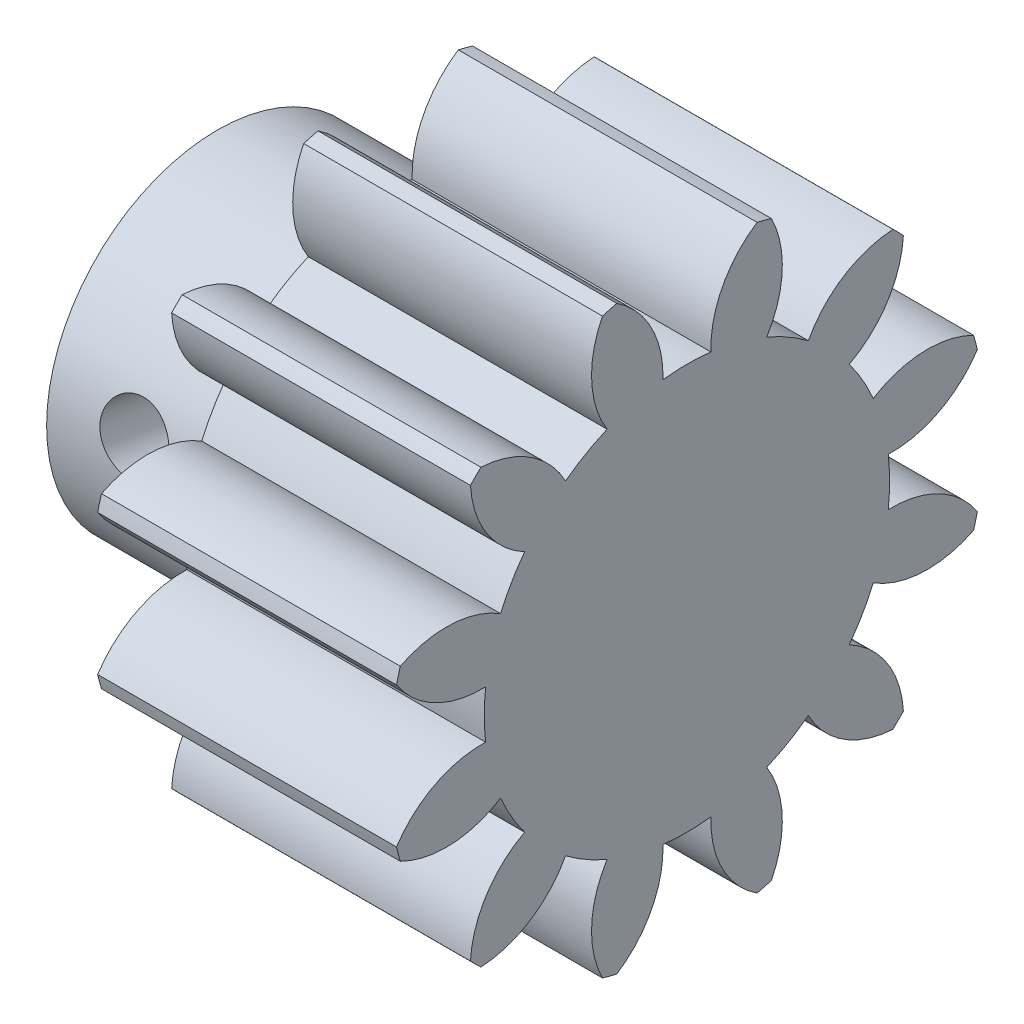
SolidWorks part; units mm, degrees
ref_plane "Plane1" through (0, 0, 0) normal (0, 0, 1) x (1, 0, 0)
ref_plane "Plane2" through (0, 0, 0) normal (0, 1, 0) x (1, 0, 0)
ref_plane "Plane3" through (0, 0, 0) normal (1, 0, 0) x (0, 0, -1)
sketch "HoldingSke" plane through (0, 0, 0) normal (0, 1, 0) x (1, 0, 0)
  line L0 (0, 0) -> (0.9781, -0.2079)
  line L1 (-15, 0) -> (100, 0) construction
  line L2 (0, 0) -> (-2.1039, 2.3779)
  line L3 (0, 0) -> (-11.863, 4.5341)
  line L4 (0, 0) -> (8.4473, 1.7955)
  line L5 (0, 0) -> (-11.2434, -4.1935)
  line L6 (0, 0) -> (-5.8027, -3.9151)
  line L7 (-2.1039, 2.3779) -> (0.4791, 14.0966)
  line L8 (-76.2, 54.61) -> (-75.5, 54.61)
  line L9 (-71.009, 38.7566) -> (-53.1078, 45.2721)
  line L10 (-76.2, 71.12) -> (104.1128, 71.12)
  line L11 (0, 0) -> (-7, 0)
  line L12 (-76.2, 101.6) -> (-76.162, 101.6)
  line L13 (24.9733, 27.94) -> (52.9518, 28.4284)
  line L14 (24.9733, 27.94) -> (24.9743, 27.94)
  line L15 (24.9733, 27.94) -> (100.4006, 29.5858)
  line L16 (-63.627, -1) -> (-12.827, -1)
  circle A0 centre (0, 0) radius 2
  circle A1 centre (0, 0) radius 4
  circle A2 centre (0, 0) radius 4
  circle A3 centre (0, 0) radius 2
  dimension "MHD" = 8
  dimension "Hub_dia" = 8
  dimension "Bore" = 4
  dimension "MBD" = 4
  dimension "Num_teeth" = 12
  dimension "Pitch" = 1
  dimension "Overall_len" = 12
  dimension "Show_teeth" = 12
  dimension "Thickness" = 7
  dimension "OAL" = 12.0001
  dimension "T_dim" = 0.7
  dimension "Ap" = 20
  dimension "H" = 19.05
  dimension "Pitch_radius" = 180.3128
  dimension "Width" = 7
  dimension "Backlash" = 0.038
  dimension "Addendum_fac" = 1
  dimension "Dedendum_fac" = 1.25
  dimension "Clearance_fac" = 0.25
  dimension "Dedendum_add" = 0.001
  dimension "Module" = 1
sketch "BasProSke" plane through (0, 0, 0) normal (0, 1, 0) x (1, 0, 0)
  line L0 (-10, 0) -> (60, 0) construction
  line L1 (0, 0) -> (0, 7)
  line L2 (0, 0) -> (7, 0)
  line L3 (7, 0) -> (7, 7)
  line L4 (7, 7) -> (0, 7)
  dimension "Thickness" = 7
  dimension "Diameter" = 14
revolve "Base-Revolve" add sketch "BasProSke" angle 360 about L0
sketch "TooCutSke" plane through (0, 0, 0) normal (1, 0, 0) x (0, 0, -1)
  line L1 (0, 0) -> (0, 107) construction
  line L2 (0, 0) -> (-0.8496, 5.9395) construction
  line L3 (0, 0) -> (-3.0836, 11.5081) construction
  line L4 (-0.8496, 5.9395) -> (-1.5418, 5.7541) construction
  arc A0 (0.5622, 4.7156) -> (-0.5622, 4.7156) centre (0, 0) ccw
  arc A1 (1.6729, 6.8233) -> (-1.6729, 6.8233) centre (0, 0) ccw
  circle A2 centre (0, 0) radius 6 construction
  circle A3 centre (0, 0) radius 5.6382 construction
  arc A4 (-0.5622, 4.7156) -> (-1.6729, 6.8233) centre (-2.9608, 4.7982) ccw
  arc A5 (1.6729, 6.8233) -> (0.5622, 4.7156) centre (2.9608, 4.7982) ccw
  dimension "Root_dia" = 9.498
  dimension "Overcut_dia" = 14.0508
  dimension "Pitch_dia" = 12
  dimension "Base_dia" = 11.2763
  dimension "Flank_rad" = 2.4
  dimension "Half_ang" = 15
  dimension "Half_CT" = 0.7167
extrude "ToothCut" cut sketch "TooCutSke" along normal through all
fillet "Breaks" [suppressed] radius 0.02
fillet "RootFillets" [suppressed] radius 0.251
pattern_circular "TeethCuts" count 12 every 30 about axis through (-10, 0, 0) along (1, 0, 0) of "ToothCut", "RootFillets", "Breaks"
sketch "HubNeaOneSke" plane through (0, 0, 0) normal (-1, 0, 0) x (0, 0, 1)
  circle A0 centre (0, 0) radius 4
  dimension "Diameter" = 8
extrude "HubNearOne" add sketch "HubNeaOneSke" along normal blind 4
sketch "HubNeaBotSke" plane through (0, 0, 0) normal (-1, 0, 0) x (0, 0, 1)
  circle A0 centre (0, 0) radius 4
  dimension "Diameter" = 8
extrude "HubNearBoth" [suppressed] add sketch "HubNeaBotSke" along normal blind 2.5
ref_plane "FarPln" through (7, 0, 0) normal (1, 0, 0) x (0, 0, -1)
sketch "HubFarSke" plane through (7, 0, 0) normal (1, 0, 0) x (0, 0, -1)
  circle A0 centre (0, 0) radius 4
  dimension "Diameter" = 8
extrude "HubFar" [suppressed] add sketch "HubFarSke" along normal blind 2.5
sketch "BorSke" plane through (0, 0, 0) normal (1, 0, 0) x (0, 0, -1)
  circle A0 centre (0, 0) radius 2
  dimension "Diameter" = 4
extrude "Bore" cut sketch "BorSke" along normal mid plane 24.0001
sketch "KeySke" plane through (0, 0, 0) normal (1, 0, 0) x (0, 0, -1)
  line L0 (-0.8, 0) -> (-0.8, 2.7)
  line L1 (-0.8, 2.7) -> (0.8, 2.7)
  line L2 (0.8, 2.7) -> (0.8, 0)
  line L3 (0, 0) -> (0, 34) construction
  line L4 (-0.8, 0) -> (0.8, 0)
  dimension "Offset" = 2.7
  dimension "Width" = 1.6
extrude "Keyway" [suppressed] cut sketch "KeySke" along normal mid plane 24.0001
pattern_circular "Keyway2" [suppressed] count 2 every 90 about axis through (-10, 0, 0) along (1, 0, 0)
sketch "Esquisse1" plane through (7, 0, 0) normal (1, 0, 0) x (0, 0, -1)
  circle A0 centre (0, 0) radius 2
  circle A1 centre (0, 0) radius 2 construction
extrude "Boss.-Extru.1" add sketch "Esquisse1" against normal blind 4
hole_wizard "Trou pour taraudage pour trou taraudé M2x0.41" positions "Esquisse3D1" profile "Esquisse5" hole size "M2x0.4" standard "Ansi Metric"
sketch3d "Esquisse3D1"
  point P0 (-2, -3.9431, 0.6723)
  dimension "D1" = 2
sketch "Esquisse5" plane through (-2, -3.9431, 0.6723) normal (1, 0, 0) x (0, -0.1681, -0.9858)
  line L0 (0, 0) -> (0, 5.4807)
  line L1 (0, 5.4807) -> (0.8, 5)
  line L2 (0.8, 5) -> (0.8, 0)
  line L5 (0.8, 0) -> (0, 0)
  line L10 (0, 5.4807) -> (-0.8, 5) construction
  line L11 (0, -6.35) -> (0, 107.95) construction
  dimension "Diamètre du perçage" = 1.6
  dimension "Profondeur du perçage" = 5
  dimension "Angle de pointe" = 118
pattern_circular "Répétition circulaire1" count 2 every 90 about axis through (12.0001, 0, 0) along (-1, 0, 0) of "Trou pour taraudage pour trou taraudé M2x0.41"
equation "' \"Module@HoldingSke\" = 6.35"
equation "' \"Num_teeth@HoldingSke\" = 12"
equation "' \"Ap@HoldingSke\" =  20"
equation "' \"Ap@HoldingSke\" = 20"
equation "' \"Width@HoldingSke\" = 0.5 * 25.4"
equation "' \"Hub_dia@HoldingSke\"= 1 * 25.4"
equation "' \"Hub_dia@HoldingSke\" = 1 * 25.4"
equation "' \"Overall_len@HoldingSke\" = 1.0 * 25.4"
equation "' \"Bore@HoldingSke\" = 0.75 * 25.4"
equation "' \"T_dim@HoldingSke\" = 0.1 * 25.4"
equation "' \"Width@KeySke\" = 0.25 * 25.4"
equation "' \"Show_teeth@HoldingSke\" = 13"
equation "' \"Backlash@HoldingSke\" = 0.009 * 25.4"
equation "' \"Addendum_fac@HoldingSke\" = 1.0"
equation "' \"Dedendum_fac@HoldingSke\" = 1.25"
equation "' \"Dedendum_add@HoldingSke\" = 0.00005 * 25.4"
equation "' \"Clearance_fac@HoldingSke\" = 0.25"
equation "\"Pitch@HoldingSke\" = 1 / \"Module@HoldingSke\""
equation "\"Overcut_dia@TooCutSke\" = (\"Num_teeth@HoldingSke\" + 2 * \"Addendum_fac@HoldingSke\") / \"Pitch@HoldingSke\" + 0.002 * 25.4"
equation "\"Pitch_dia@TooCutSke\" = \"Num_teeth@HoldingSke\" / \"Pitch@HoldingSke\""
equation "\"Base_dia@TooCutSke\" = \"Num_teeth@HoldingSke\" / \"Pitch@HoldingSke\" * cos((\"Ap@HoldingSke\"  * 3.14159265 / 180))"
equation "\"Root_dia@TooCutSke\" = (\"Num_teeth@HoldingSke\" + 2) / \"Pitch@HoldingSke\" - 2 * (\"Addendum_fac@HoldingSke\" + \"Dedendum_fac@HoldingSke\") / \"Pitch@HoldingSke\" - \"Dedendum_add@HoldingSke\" * 2"
equation "\"Half_ang@TooCutSke\" = 180 / \"Num_teeth@HoldingSke\""
equation "\"Half_CT@TooCutSke\" = \"Num_teeth@HoldingSke\" / \"Pitch@HoldingSke\" * sin((3.14159265 / 2 / \"Num_teeth@HoldingSke\")) / 2 - 7 * \"Backlash@HoldingSke\" / 4"
equation "\"Flank_rad@TooCutSke\" = \"Num_teeth@HoldingSke\" / \"Pitch@HoldingSke\" / 5"
equation "\"Radius@RootFillets\" = \"Clearance_fac@HoldingSke\" / \"Pitch@HoldingSke\" + \"Dedendum_add@HoldingSke\""
equation "\"Break_rad@Breaks\" = 0.02 / \"Pitch@HoldingSke\""
equation "\"Thickness@HoldingSke\" = \"Width@HoldingSke\""
equation "\"OAL@HoldingSke\" = \"Thickness@HoldingSke\""
equation "\"MHD@HoldingSke\" = (\"Num_teeth@HoldingSke\" + 2) / \"Pitch@HoldingSke\" - 2 * (\"Addendum_fac@HoldingSke\" + \"Dedendum_fac@HoldingSke\")  / \"Pitch@HoldingSke\" - \"Dedendum_add@HoldingSke\" * 2"
equation "\"MBD@HoldingSke\" = (\"Num_teeth@HoldingSke\" + 2) / \"Pitch@HoldingSke\" - 2 * (\"Addendum_fac@HoldingSke\" + \"Dedendum_fac@HoldingSke\")  / \"Pitch@HoldingSke\" - \"Dedendum_add@HoldingSke\" * 2 - 0.002 * 25.4"
equation "\"MHD@HoldingSke\" = ((sgn( \"MHD@HoldingSke\" - \"Hub_dia@HoldingSke\" )-1)*( \"MHD@HoldingSke\" - \"Hub_dia@HoldingSke\" ))/-2+ \"Hub_dia@HoldingSke\""
equation "\"MBD@HoldingSke\" = ((sgn( \"MBD@HoldingSke\" - \"Bore@HoldingSke\" )-1)*( \"MBD@HoldingSke\" - \"Bore@HoldingSke\" ))/-2+ \"Bore@HoldingSke\""
equation "\"OAL@HoldingSke\" = ((sgn( \"OAL@HoldingSke\" - \"Overall_len@HoldingSke\" )+1)*( \"OAL@HoldingSke\" - \"Overall_len@HoldingSke\" ))/2 + \"Overall_len@HoldingSke\" + 0.000002 * 25.4"
equation "\"Num_teeth@TeethCuts\" = int( \"Show_teeth@HoldingSke\" ) + 1"
equation "\"Num_teeth@TeethCuts\" = ((sgn( \"Num_teeth@TeethCuts\" - \"Num_teeth@HoldingSke\" )-1)*( \"Num_teeth@TeethCuts\" - \"Num_teeth@HoldingSke\" ))/-2+ \"Num_teeth@HoldingSke\""
equation "\"Num_teeth@TeethCuts\" = ((sgn( \"Num_teeth@TeethCuts\" - 2.0)+1)*( \"Num_teeth@TeethCuts\" - 2.0))/2 +2.0"
equation "\"Angle@TeethCuts\" = 360.0 / \"Num_teeth@HoldingSke\""
equation "\"Diameter@BasProSke\" = (\"Num_teeth@HoldingSke\" + 2 * \"Addendum_fac@HoldingSke\") / \"Pitch@HoldingSke\""
equation "\"Thickness@BasProSke\"  = \"Thickness@HoldingSke\""
equation "' \"Fillet_rad@BasProSke\" =  \"Thickness@HoldingSke\" * 0.05"
equation "' \"Fillet_rad@BasProSke\" = \"Thickness@HoldingSke\" * 0.05"
equation "\"MHD@HoldingSke\" = ((sgn( \"MHD@HoldingSke\" - \"Root_dia@TooCutSke\" )-1)*( \"MHD@HoldingSke\" - \"Root_dia@TooCutSke\" ))/-2+ \"Root_dia@TooCutSke\""
equation "\"Diameter@HubNeaOneSke\" = \"MHD@HoldingSke\""
equation "\"Length@HubNearOne\"=4"
equation "\"Diameter@HubNeaBotSke\" = \"MHD@HoldingSke\""
equation "\"Length@HubNearBoth\" = ( \"OAL@HoldingSke\" - \"Thickness@BasProSke\" ) / 2.0"
equation "\"Thickness@FarPln\" = \"Thickness@BasProSke\""
equation "\"Diameter@HubFarSke\" = \"MHD@HoldingSke\""
equation "\"Length@HubFar\" = ( \"OAL@HoldingSke\" - \"Thickness@BasProSke\" ) / 2.0"
equation "\"Diameter@BorSke\" = \"MBD@HoldingSke\""
equation "\"D1@Bore\" = \"OAL@HoldingSke\" * 2.0"
equation "\"D1@Keyway\" = \"OAL@HoldingSke\" * 2.0"
equation "\"Offset@KeySke\" = \"T_dim@HoldingSke\" + \"MBD@HoldingSke\" / 2.0"
